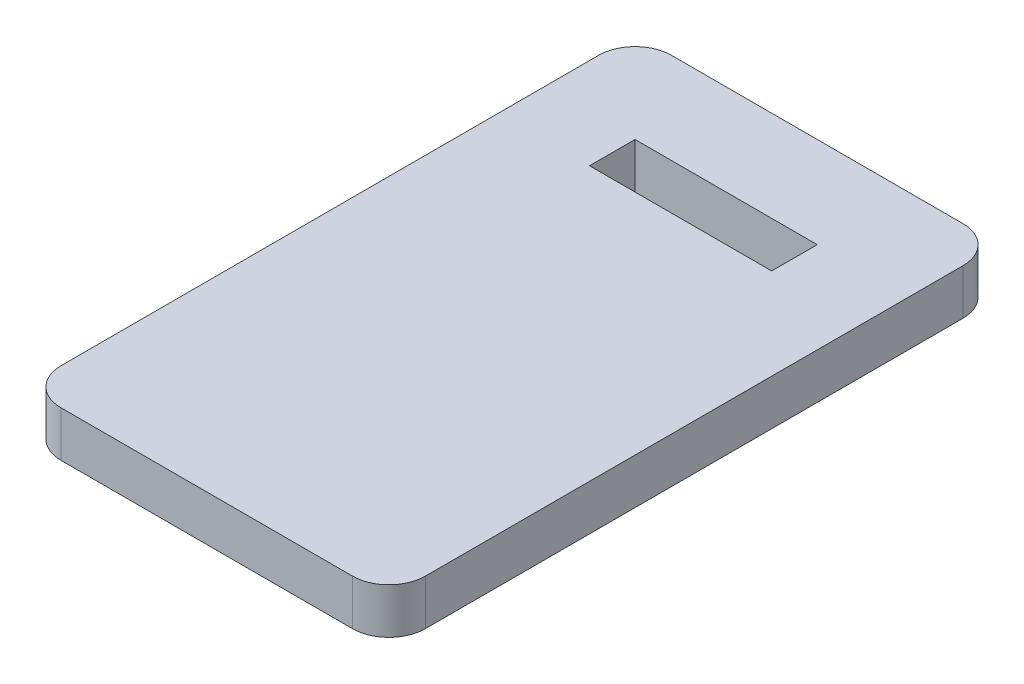
SolidWorks part; units mm, degrees
material "Acrylic (Medium-high impact)"
ref_plane "Front Plane" through (0, 0, 0) normal (0, 0, 1) x (1, 0, 0)
ref_plane "Top Plane" through (0, 0, 0) normal (0, 1, 0) x (1, 0, 0)
ref_plane "Right Plane" through (0, 0, 0) normal (1, 0, 0) x (0, 0, -1)
ref_plane "Plane1" through (0, 0, 0) normal (0, 1, 0) x (1, 0, 0)
sketch "Sketch1" plane through (0, 0, 0) normal (0, 1, 0) x (1, 0, 0)
  line L1 (0, 0) -> (25.4, 0)
  line L2 (0, 0) -> (0, 42.555)
  line L3 (0, 42.555) -> (25.4, 42.555)
  line L4 (25.4, 0) -> (25.4, 42.555)
  dimension "D1" = 42.555
  dimension "D2" = 25.4
extrude "Boss-Extrude1" add sketch "Sketch1" along normal blind 3.175
ref_plane "Plane2" through (0, 3.175, 0) normal (0, 1, 0) x (1, 0, 0)
sketch "Sketch2" plane through (0, 3.175, 0) normal (0, 1, 0) x (1, 0, 0)
  line L0 (0, 42.555) -> (0, 0) construction
  line L1 (6.35, 33.03) -> (19.05, 33.03)
  line L2 (6.35, 33.03) -> (6.35, 36.205)
  line L3 (6.35, 36.205) -> (19.05, 36.205)
  line L4 (19.05, 33.03) -> (19.05, 36.205)
  line L5 (25.4, 0) -> (25.4, 42.555) construction
  line L7 (25.4, 42.555) -> (0, 42.555) construction
  dimension "D1" = 6.35
  dimension "D2" = 6.35
  dimension "D3" = 6.35
  dimension "D4" = 3.175
extrude "Cut-Extrude1" cut sketch "Sketch2" against normal through all
fillet "Fillet1" radius 2.54 4 edges at (0, 1.5875, -42.555) (25.4, 1.5875, -42.555) (25.4, 1.5875, 0) (0, 1.5875, 0)
